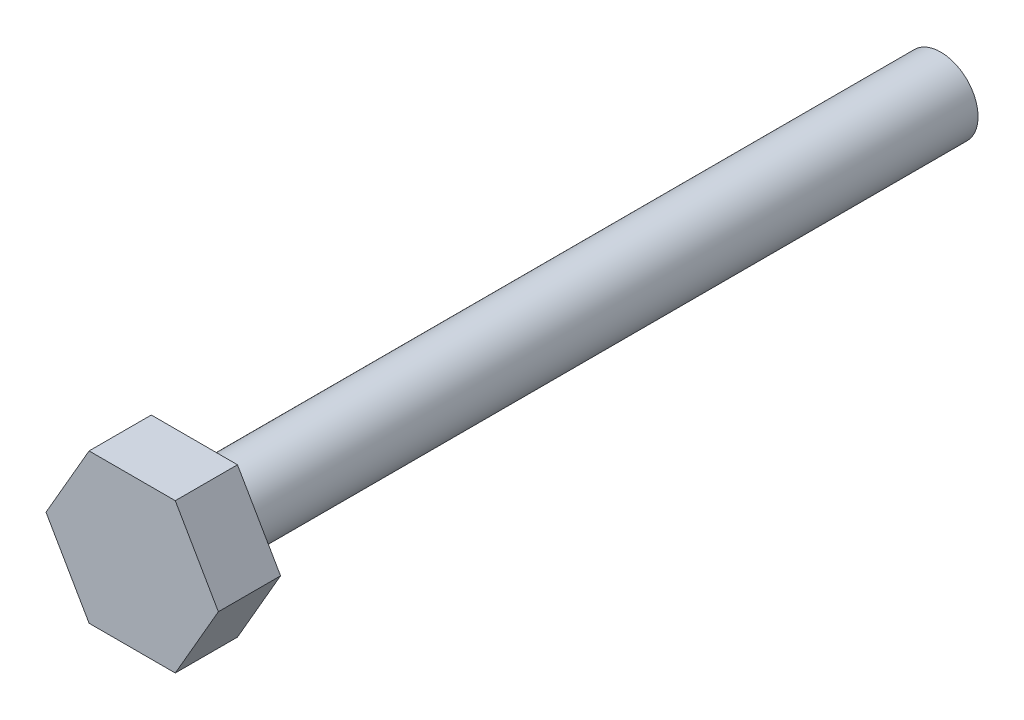
SolidWorks part; units mm, degrees
ref_plane "Front Plane" through (0, 0, 0) normal (0, 0, 1) x (1, 0, 0)
ref_plane "Top Plane" through (0, 0, 0) normal (0, 1, 0) x (1, 0, 0)
ref_plane "Right Plane" through (0, 0, 0) normal (1, 0, 0) x (0, 0, -1)
sketch "Sketch1" plane through (0, 0, 0) normal (0, 0, 1) x (1, 0, 0)
  line L1 (3.4641, 6) -> (-3.4641, 6)
  line L2 (-3.4641, 6) -> (-6.9282, 0)
  line L3 (-6.9282, 0) -> (-3.4641, -6)
  line L4 (-3.4641, -6) -> (3.4641, -6)
  line L5 (3.4641, -6) -> (6.9282, 0)
  line L6 (6.9282, 0) -> (3.4641, 6)
  circle A0 centre (0, 0) radius 6 construction
  dimension "D1" = 12
extrude "Boss-Extrude1" add sketch "Sketch1" along normal blind 5
sketch "Sketch2" plane through (0, 0, 0) normal (0, 0, -1) x (-1, 0, 0)
  circle A0 centre (0, 0) radius 3
  dimension "D1" = 6
extrude "Boss-Extrude2" add sketch "Sketch2" along normal blind 60
